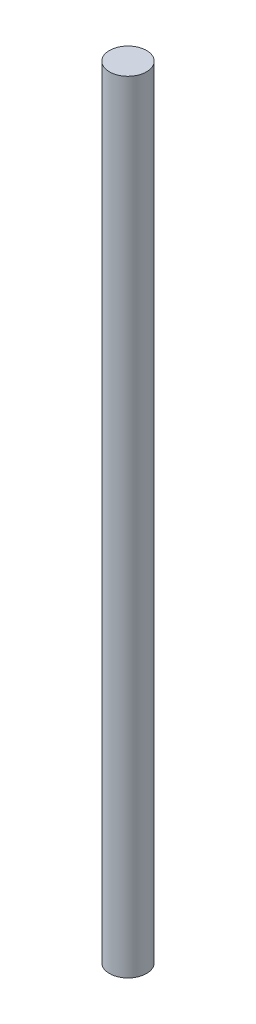
SolidWorks part; units mm, degrees
ref_plane "前视基准面" through (0, 0, 0) normal (0, 0, 1) x (1, 0, 0)
ref_plane "上视基准面" through (0, 0, 0) normal (0, 1, 0) x (1, 0, 0)
ref_plane "右视基准面" through (0, 0, 0) normal (1, 0, 0) x (0, 0, -1)
other "Configuration Table"
sketch "草图2" plane through (0, 0, 0) normal (0, 1, 0) x (1, 0, 0)
  circle A0 centre (0, 0) radius 1.9
  dimension "D1" = 3.8
extrude "凸台-拉伸1" add sketch "草图2" along normal blind 80
